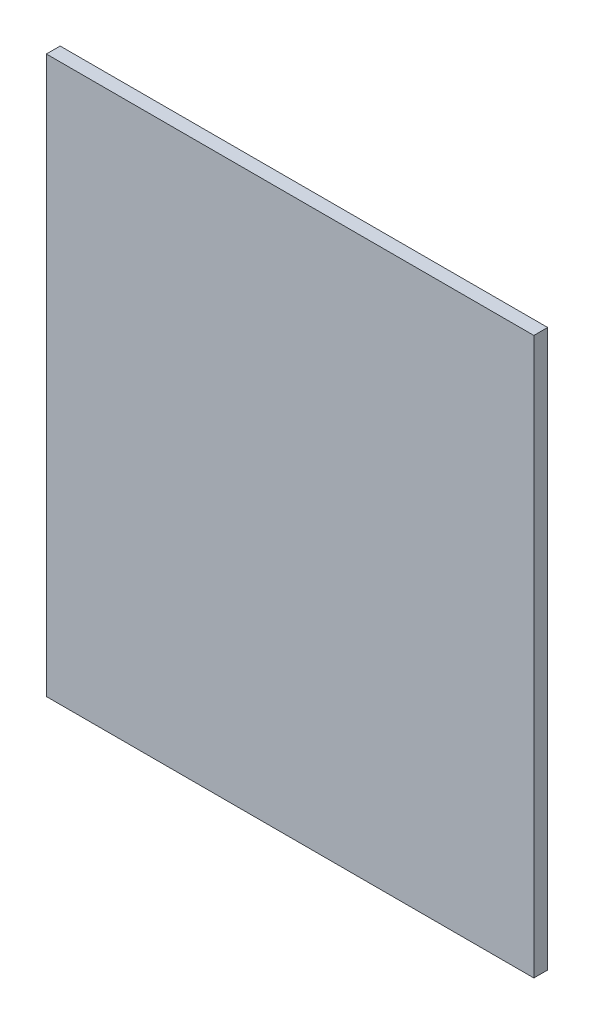
SolidWorks part; units mm, degrees
ref_plane "前视基准面" through (0, 0, 0) normal (0, 0, 1) x (1, 0, 0)
ref_plane "上视基准面" through (0, 0, 0) normal (0, 1, 0) x (1, 0, 0)
ref_plane "右视基准面" through (0, 0, 0) normal (1, 0, 0) x (0, 0, -1)
other "Configuration Table"
sketch "草图1" plane through (0, 0, 0) normal (0, 0, 1) x (1, 0, 0)
  line L0 (0, 0) -> (106, 0)
  line L1 (106, 0) -> (106, 121)
  line L2 (106, 121) -> (0, 121)
  line L3 (0, 121) -> (0, 0)
  dimension "width" = 106
  dimension "height" = 121
extrude "BlockExtrude" add sketch "草图1" along normal blind 3
